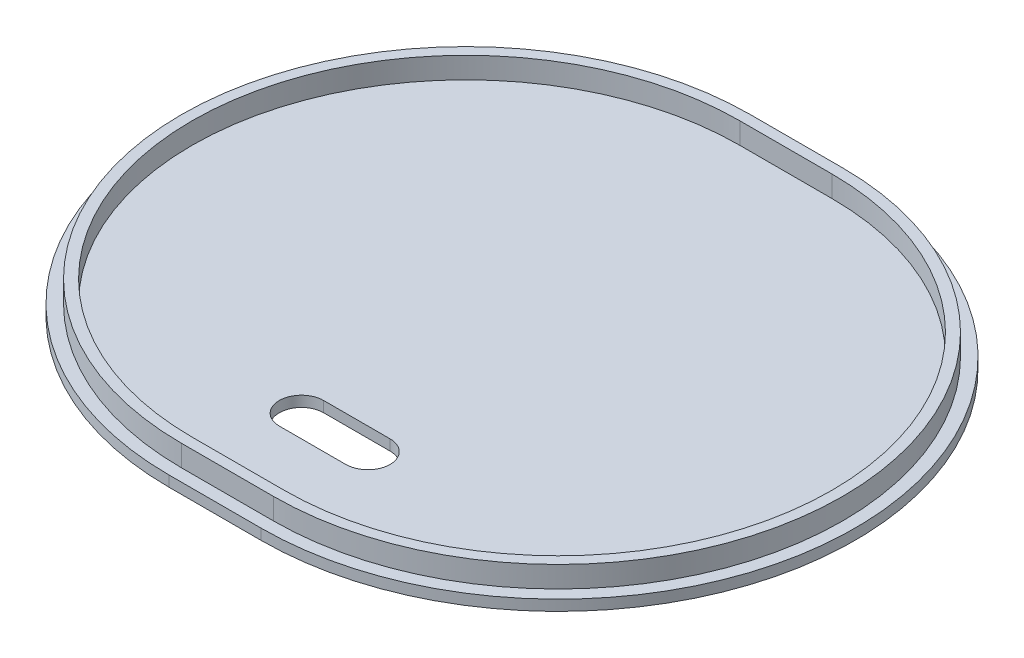
SolidWorks part; units mm, degrees
ref_plane "Front Plane" through (0, 0, 0) normal (0, 0, 1) x (1, 0, 0)
ref_plane "Top Plane" through (0, 0, 0) normal (0, 1, 0) x (1, 0, 0)
ref_plane "Right Plane" through (0, 0, 0) normal (1, 0, 0) x (0, 0, -1)
sketch "Sketch1" plane through (0, 0, 0) normal (0, 1, 0) x (1, 0, 0)
  line L0 (0, 0) -> (77.4, 0) construction
  line L1 (0, 0) -> (0, 115.9337) construction
  line L2 (-10.4, 67) -> (10.4, 67)
  line L3 (-10.4, -67) -> (10.4, -67)
  arc A0 (10.4, -67) -> (10.4, 67) centre (10.4, 0) ccw
  arc A1 (-10.4, -67) -> (-10.4, 67) centre (-10.4, 0) cw
  dimension "D1" = 134
  dimension "D2" = 77.4
extrude "Boss-Extrude1" add sketch "Sketch1" along normal blind 2.4
sketch "Sketch2" plane through (0, 2.4, 0) normal (0, 1, 0) x (1, 0, 0)
  line L0 (0, 0) -> (0, 80.1975) construction
  line L1 (-10.4, 67) -> (10.4, 67) construction
  line L2 (77.4, 0) -> (10.4, 0) construction
  line L3 (-10.4, -67) -> (10.4, -67) construction
  line L4 (-10.4, 64.2) -> (10.4, 64.2)
  line L5 (-10.4, -64.2) -> (10.4, -64.2)
  line L6 (-10.4, 61.8) -> (10.4, 61.8)
  line L7 (-10.4, -61.8) -> (10.4, -61.8)
  arc A0 (10.4, -67) -> (10.4, 67) centre (10.4, 0) ccw construction
  arc A1 (-10.4, -67) -> (-10.4, 67) centre (-10.4, 0) cw construction
  arc A2 (-10.4, -64.2) -> (-10.4, 64.2) centre (-10.4, 0) cw
  arc A3 (10.4, -64.2) -> (10.4, 64.2) centre (10.4, 0) ccw
  arc A4 (-10.4, -61.8) -> (-10.4, 61.8) centre (-10.4, 0) cw
  arc A5 (10.4, -61.8) -> (10.4, 61.8) centre (10.4, 0) ccw
  dimension "D2" = 134
  dimension "D1" = 77.4
  dimension "D3" = 2.8
  dimension "D4" = 2.4
extrude "Boss-Extrude2" add sketch "Sketch2" along normal blind 4.8
sketch "Sketch3" plane through (0, 2.4, 0) normal (0, 1, 0) x (1, 0, 0)
  line L0 (0, 0) -> (77.4, 0) construction
  line L1 (0, 0) -> (0, -40) construction
  line L2 (-7.5, -40) -> (7.5, -40) construction
  line L3 (-7.5, -35) -> (7.5, -35)
  line L4 (-7.5, -45) -> (7.5, -45)
  arc A0 (10.4, -67) -> (10.4, 67) centre (10.4, 0) ccw construction
  arc A1 (-7.5, -35) -> (-7.5, -45) centre (-7.5, -40) ccw
  arc A2 (7.5, -45) -> (7.5, -35) centre (7.5, -40) ccw
  point P10 (0, -40)
extrude "Cut-Extrude1" cut sketch "Sketch3" against normal through all
